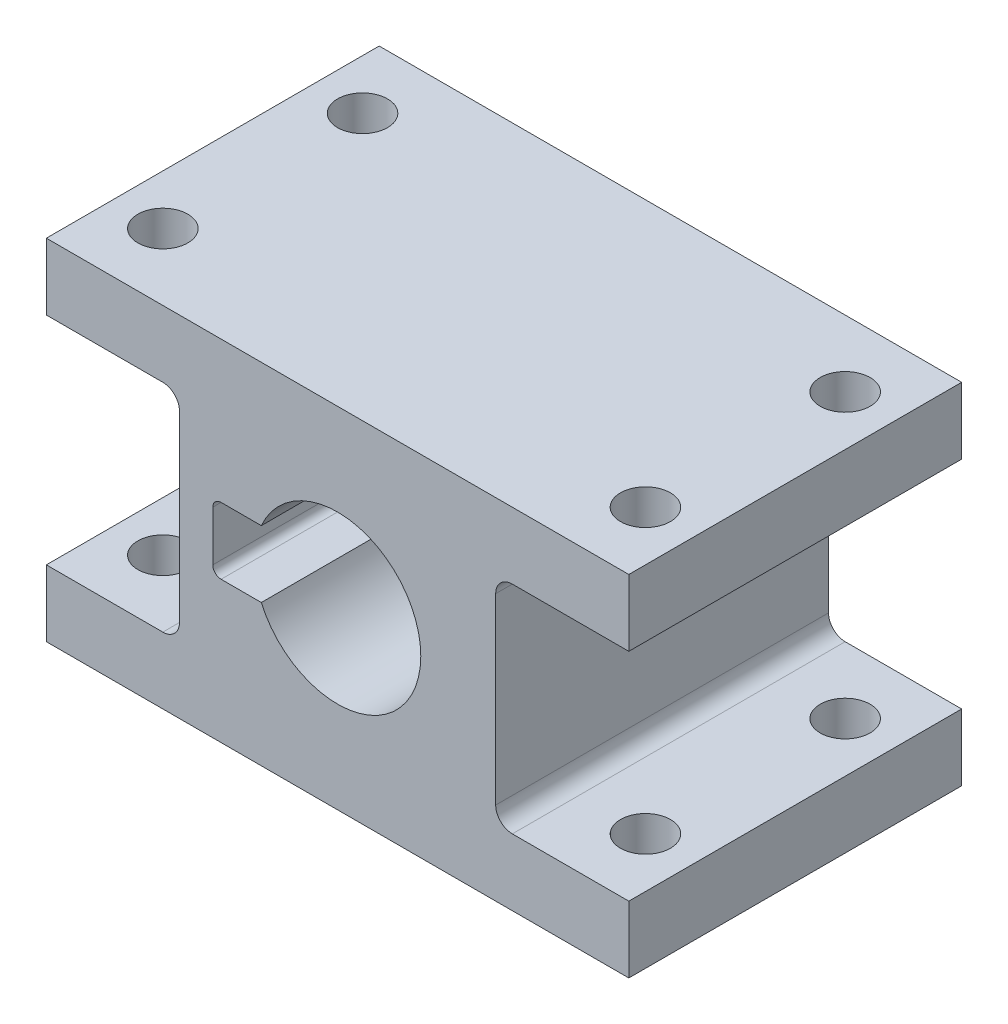
SolidWorks part; units mm, degrees
material "POM 乙缩醛共聚物"
ref_plane "前视基准面" through (0, 0, 0) normal (0, 0, 1) x (1, 0, 0)
ref_plane "上视基准面" through (0, 0, 0) normal (0, 1, 0) x (1, 0, 0)
ref_plane "右视基准面" through (0, 0, 0) normal (1, 0, 0) x (0, 0, -1)
sketch "草图1" plane through (0, 0, 0) normal (0, 0, 1) x (1, 0, 0)
  line L1 (-17.5, 10.5) -> (17.5, 10.5)
  line L2 (-17.5, 10.5) -> (-17.5, -10.5)
  line L3 (-17.5, -10.5) -> (17.5, -10.5)
  line L4 (17.5, 10.5) -> (17.5, -10.5)
  line L5 (-17.5, 10.5) -> (17.5, -10.5) construction
  line L6 (-17.5, -10.5) -> (17.5, 10.5) construction
  point P0 (0, 0)
  dimension "D1" = 35
  dimension "D2" = 21
extrude "凸台-拉伸1" add sketch "草图1" along normal blind 20
sketch "草图2" plane through (0, 0, 20) normal (0, 0, 1) x (1, 0, 0)
  line L0 (-17.5, 0) -> (17.5, 0) construction
  line L1 (-17.5, 10.5) -> (-17.5, -10.5) construction
  line L2 (17.5, -10.5) -> (17.5, 10.5) construction
  circle A0 centre (0, 0) radius 5
  dimension "D1" = 17.5
  dimension "D2" = 10
extrude "切除-拉伸1" cut sketch "草图2" against normal blind 18
sketch "草图3" plane through (0, 0, 20) normal (0, 0, 1) x (1, 0, 0)
  line L9 (-7.5, 2) -> (0, 2)
  line L10 (-7.5, 2) -> (-7.5, -2)
  line L11 (-7.5, -2) -> (0, -2)
  line L12 (0, 2) -> (0, -2)
  point P4 (0, 0)
  dimension "D1" = 7.5
  dimension "D2" = 4
extrude "切除-拉伸2" cut sketch "草图3" against normal blind 18
fillet "圆角1" radius 0.5 2 edges at (-7.5, 2, 11) (-7.5, -2, 11)
sketch "草图6" plane through (0, 0, 20) normal (0, 0, 1) x (1, 0, 0)
  line L0 (-17.5, 0) -> (17.5, 0) construction
  line L1 (-17.5, 10.5) -> (-17.5, -10.5) construction
  line L2 (17.5, -10.5) -> (17.5, 10.5) construction
  line L3 (0, 10.5) -> (0, 0) construction
  line L4 (17.5, 10.5) -> (-17.5, 10.5) construction
sketch "草图7" plane through (0, 0, 20) normal (0, 0, 1) x (1, 0, 0)
  line L0 (0, 10.5) -> (0, -10.5) construction
  line L1 (-17.5, -10.5) -> (17.5, -10.5) construction
  line L2 (17.5, 10.5) -> (-17.5, 10.5) construction
  line L3 (-17.5, 6.5) -> (-9.5, 6.5)
  line L4 (-17.5, 6.5) -> (-17.5, -6.5)
  line L5 (-17.5, -6.5) -> (-9.5, -6.5)
  line L6 (-9.5, 6.5) -> (-9.5, -6.5)
  line L7 (9.5, 6.5) -> (9.5, -6.5)
  line L8 (17.5, -6.5) -> (9.5, -6.5)
  line L9 (17.5, 6.5) -> (17.5, -6.5)
  line L10 (17.5, 6.5) -> (9.5, 6.5)
  dimension "D1" = 4
  dimension "D2" = 8
extrude "切除-拉伸3" cut sketch "草图7" against normal through all
fillet "圆角2" radius 1 4 edges at (9.5, 6.5, 10) (9.5, -6.5, 10) (-9.5, -6.5, 10) (-9.5, 6.5, 10)
sketch "草图8" plane through (0, 10.5, 0) normal (0, 1, 0) x (1, 0, 0)
  line L0 (-14.5, 0) -> (-14.5, -20) construction
  line L1 (17.5, 0) -> (-17.5, 0) construction
  line L2 (17.5, -20) -> (-17.5, -20) construction
  line L3 (0, 0) -> (0, -20) construction
  line L4 (-17.5, -20) -> (-17.5, 0) construction
  line L5 (-17.5, -10) -> (-14.5, -10) construction
  circle A0 centre (-14.5, -4) radius 1.5
  circle A1 centre (-14.5, -16) radius 1.5
  circle A2 centre (14.5, -16) radius 1.5
  circle A3 centre (14.5, -4) radius 1.5
  dimension "D2" = 3
  dimension "D1" = 3
  dimension "D3" = 6
extrude "切除-拉伸4" cut sketch "草图8" against normal through all
